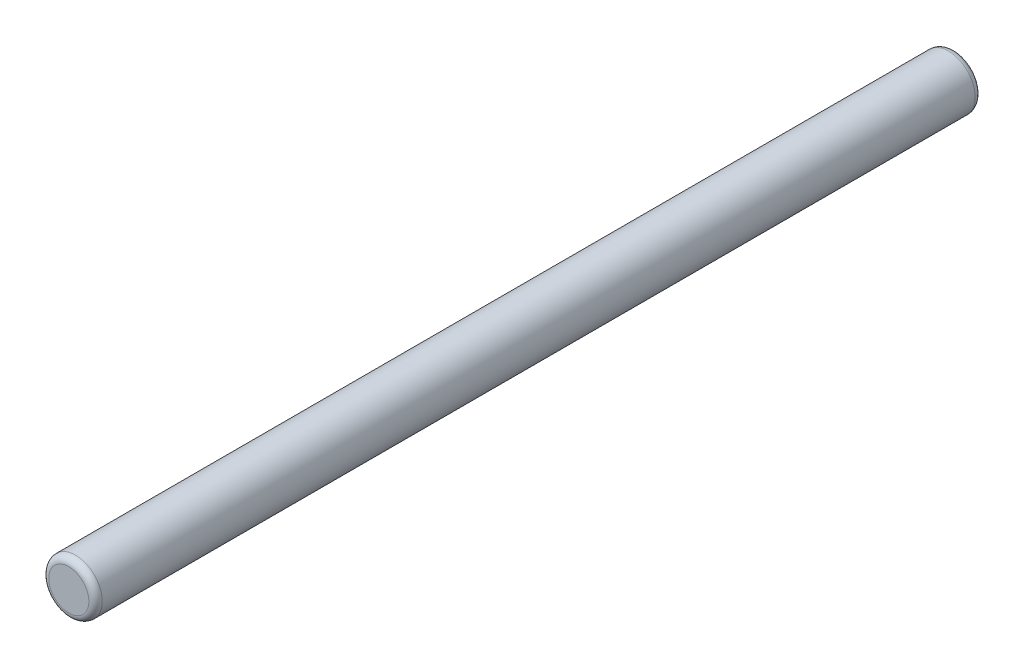
SolidWorks part; units mm, degrees
ref_plane "Front Plane" through (0, 0, 0) normal (0, 0, 1) x (1, 0, 0)
ref_plane "Top Plane" through (0, 0, 0) normal (0, 1, 0) x (1, 0, 0)
ref_plane "Right Plane" through (0, 0, 0) normal (1, 0, 0) x (0, 0, -1)
sketch "Sketch1" plane through (0, 0, 0) normal (0, 0, 1) x (1, 0, 0)
  circle A0 centre (0, 0) radius 4
  dimension "D1" = 8
extrude "Boss-Extrude1" add sketch "Sketch1" along normal blind 132.5
fillet "Fillet1" radius 1 2 edges at (4, 0, 132.5) (4, 0, 0)
